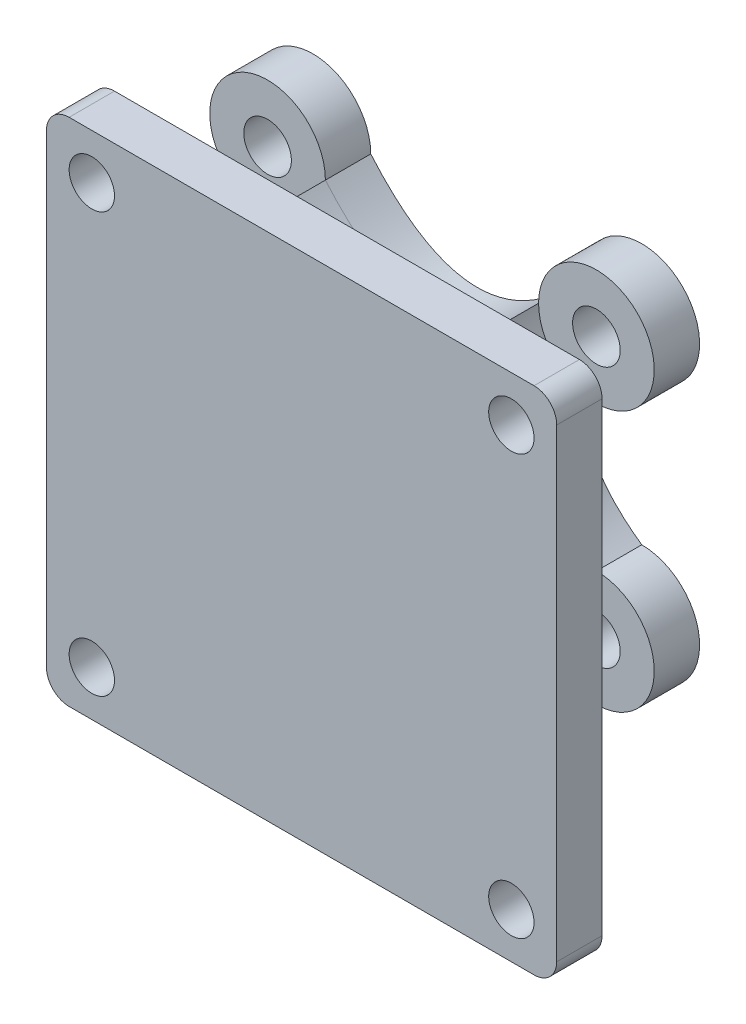
SolidWorks part; units mm, degrees
ref_plane "前基準面" through (0, 0, 0) normal (0, 0, 1) x (1, 0, 0)
ref_plane "上基準面" through (0, 0, 0) normal (0, 1, 0) x (1, 0, 0)
ref_plane "右基準面" through (0, 0, 0) normal (1, 0, 0) x (0, 0, -1)
sketch "草圖1" plane through (0, 0, 0) normal (0, 0, 1) x (1, 0, 0)
  line L0 (0, 0) -> (11.5909, 0) construction
  line L1 (-14.5, 11.5) -> (14.5, 11.5) construction
  line L2 (-14.5, 11.5) -> (-14.5, -11.5) construction
  line L3 (-14.5, -11.5) -> (14.5, -11.5) construction
  line L4 (14.5, 11.5) -> (14.5, -11.5) construction
  line L5 (-14.5, 11.5) -> (14.5, -11.5) construction
  line L6 (-14.5, -11.5) -> (14.5, 11.5) construction
  line L7 (0, 0) -> (0, -5.1103) construction
  circle A0 centre (-14.5, 11.5) radius 2.1
  circle A1 centre (-14.5, -11.5) radius 2.1
  circle A2 centre (14.5, -11.5) radius 2.1
  circle A3 centre (14.5, 11.5) radius 2.1
  circle A4 centre (-14.5, 11.5) radius 5.1
  circle A5 centre (-14.5, -11.5) radius 5.1
  circle A6 centre (14.5, 11.5) radius 5.1
  circle A7 centre (14.5, -11.5) radius 5.1
  spline S0 degree 2 poles (-9.4, 11.5) (0, 0.5) (9.4, 11.5) knots 0 0 0 1 1 1
  spline S1 degree 2 poles (-9.4, -11.5) (0, -0.5) (9.4, -11.5) knots 0 0 0 1 1 1
  spline S2 degree 2 poles (-14.5, 6.4) (-5.5, 0) (-14.5, -6.4) knots 0 0 0 1 1 1
  spline S3 degree 2 poles (14.5, 6.4) (5.5, 0) (14.5, -6.4) knots 0 0 0 1 1 1
  point P0 (0, 0)
  point P25 (-10.6771, 0)
  dimension "D3" = 4.2
  dimension "D4" = 4.2
  dimension "D5" = 4.2
  dimension "D6" = 4.2
  dimension "D7" = 3
  dimension "D8" = 3
  dimension "D9" = 3
  dimension "D10" = 3
  dimension "D1" = 29
  dimension "D2" = 23
  dimension "D11" = 6
  dimension "D12" = 10
extrude "填料-伸長1" add sketch "草圖1" along normal blind 4 contours A4 A0 | S3 A6 S0 A4 S2 A5 S1 A7 | A6 A3 | A7 A2 | A5 A1
sketch "草圖2" plane through (0, 0, 4) normal (0, 0, 1) x (1, 0, 0)
  arc A0 (-14.5, 6.4) -> (-9.4, 11.5) centre (-14.5, 11.5) ccw
  arc A1 (9.4, 11.5) -> (14.5, 6.4) centre (14.5, 11.5) ccw
  arc A2 (14.5, -6.4) -> (9.4, -11.5) centre (14.5, -11.5) ccw
  arc A3 (-9.4, -11.5) -> (-14.5, -6.4) centre (-14.5, -11.5) ccw
  arc A4 (-9.4, 11.5) -> (-14.5, 6.4) centre (-14.5, 11.5) ccw
  arc A5 (-14.5, -6.4) -> (-9.4, -11.5) centre (-14.5, -11.5) ccw
  arc A6 (9.4, -11.5) -> (14.5, -6.4) centre (14.5, -11.5) ccw
  arc A7 (14.5, 6.4) -> (9.4, 11.5) centre (14.5, 11.5) ccw
  parabola Q4 (-14.5, 6.4) -> (-14.5, -6.4) focus (-12.2756, 0) apex (-10, 0)
  parabola Q5 (-9.4, -11.5) -> (9.4, -11.5) focus (0, -10.0164) apex (0, -6)
  parabola Q6 (14.5, -6.4) -> (14.5, 6.4) focus (12.2756, 0) apex (10, 0)
  parabola Q7 (9.4, 11.5) -> (-9.4, 11.5) focus (0, 10.0164) apex (0, 6)
  parabola Q8 (-14.5, 6.4) -> (-14.5, -6.4) focus (-12.2756, 0) apex (-10, 0)
  parabola Q9 (-9.4, -11.5) -> (9.4, -11.5) focus (0, -10.0164) apex (0, -6)
  parabola Q10 (14.5, -6.4) -> (14.5, 6.4) focus (12.2756, 0) apex (10, 0)
  parabola Q11 (9.4, 11.5) -> (-9.4, 11.5) focus (0, 10.0164) apex (0, 6)
  dimension "D1" = 0
extrude "填料-伸長2" add sketch "草圖2" along normal blind 11.5
sketch "草圖3" plane through (0, 0, 15.5) normal (0, 0, 1) x (1, 0, 0)
  line L0 (0, 0) -> (0, -6) construction
  line L1 (-18.5, 12.5) -> (18.5, 12.5) construction
  line L2 (-18.5, 12.5) -> (-18.5, -24.5) construction
  line L3 (-18.5, -24.5) -> (18.5, -24.5) construction
  line L4 (18.5, 12.5) -> (18.5, -24.5) construction
  line L5 (-18.5, 12.5) -> (18.5, -24.5) construction
  line L6 (-18.5, -24.5) -> (18.5, 12.5) construction
  line L7 (-20.5, 16.5) -> (20.5, 16.5)
  line L8 (-22.5, 14.5) -> (-22.5, -26.5)
  line L9 (-20.5, -28.5) -> (20.5, -28.5)
  line L10 (22.5, 14.5) -> (22.5, -26.5)
  line L11 (-22.5, 16.5) -> (22.5, -28.5) construction
  line L12 (-22.5, -28.5) -> (22.5, 16.5) construction
  circle A0 centre (-18.5, 12.5) radius 2
  circle A1 centre (-18.5, -24.5) radius 2
  circle A2 centre (18.5, -24.5) radius 2
  circle A3 centre (18.5, 12.5) radius 2
  arc A4 (20.5, 16.5) -> (22.5, 14.5) centre (20.5, 14.5) cw
  arc A5 (20.5, -28.5) -> (22.5, -26.5) centre (20.5, -26.5) ccw
  arc A6 (-22.5, -26.5) -> (-20.5, -28.5) centre (-20.5, -26.5) ccw
  arc A7 (-20.5, 16.5) -> (-22.5, 14.5) centre (-20.5, 14.5) ccw
  point P10 (0, -6)
  point P27 (0, 0)
  dimension "D3" = 4
  dimension "D4" = 4
  dimension "D5" = 4
  dimension "D6" = 4
  dimension "D9" = 2
  dimension "D1" = 37
  dimension "D2" = 37
  dimension "D7" = 45
  dimension "D8" = 45
  dimension "D10" = 6
extrude "填料-伸長3" add sketch "草圖3" against normal blind 4
